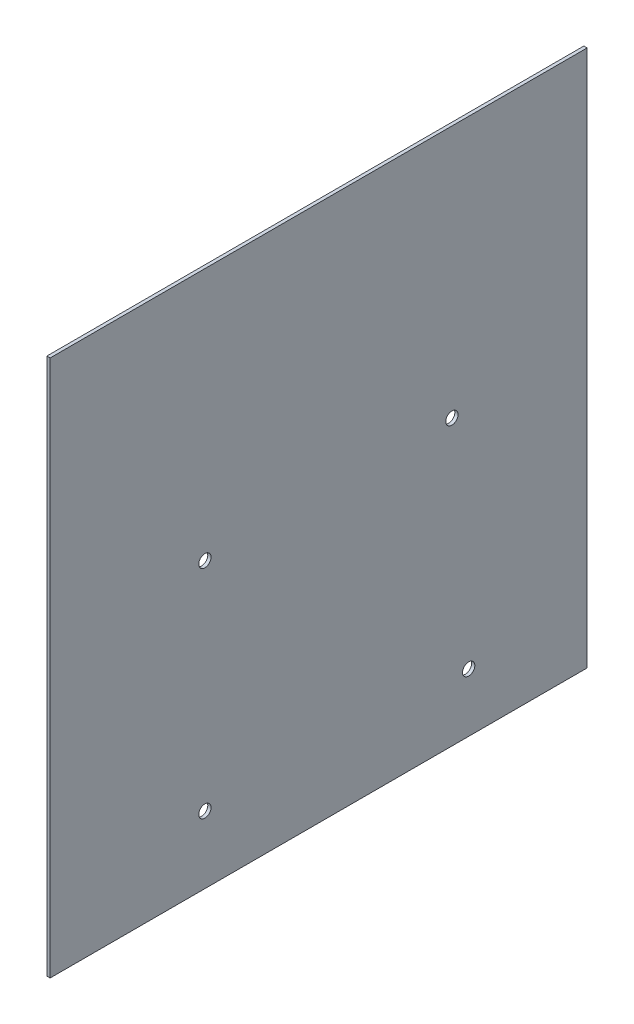
SolidWorks part; units mm, degrees
ref_plane "Front Plane" through (0, 0, 0) normal (0, 0, 1) x (1, 0, 0)
ref_plane "Top Plane" through (0, 0, 0) normal (0, 1, 0) x (1, 0, 0)
ref_plane "Right Plane" through (0, 0, 0) normal (1, 0, 0) x (0, 0, -1)
sketch "Sketch2" plane through (0, 0, 0) normal (1, 0, 0) x (0, 0, -1)
  line L1 (-65.4, 65.4) -> (65.4, 65.4)
  line L2 (-65.4, 65.4) -> (-65.4, -65.4)
  line L3 (-65.4, -65.4) -> (65.4, -65.4)
  line L4 (65.4, 65.4) -> (65.4, -65.4)
  line L5 (-65.4, 65.4) -> (65.4, -65.4) construction
  line L6 (-65.4, -65.4) -> (65.4, 65.4) construction
  point P0 (0, 0)
  dimension "D1" = 130.8
  dimension "D2" = 130.8
extrude "Boss-Extrude1" add sketch "Sketch2" along normal blind 0.8
sketch "Sketch3" plane through (0, 0, 0) normal (1, 0, 0) x (0, 0, -1)
  circle A0 centre (-27.7049, 3.7878) radius 1.5
  circle A1 centre (32.4667, 3.7878) radius 1.5
  circle A2 centre (-27.7049, -49.0247) radius 1.5
  circle A3 centre (36.5463, -51.1892) radius 1.5
extrude "Cut-Extrude1" cut sketch "Sketch3" along normal blind 10
